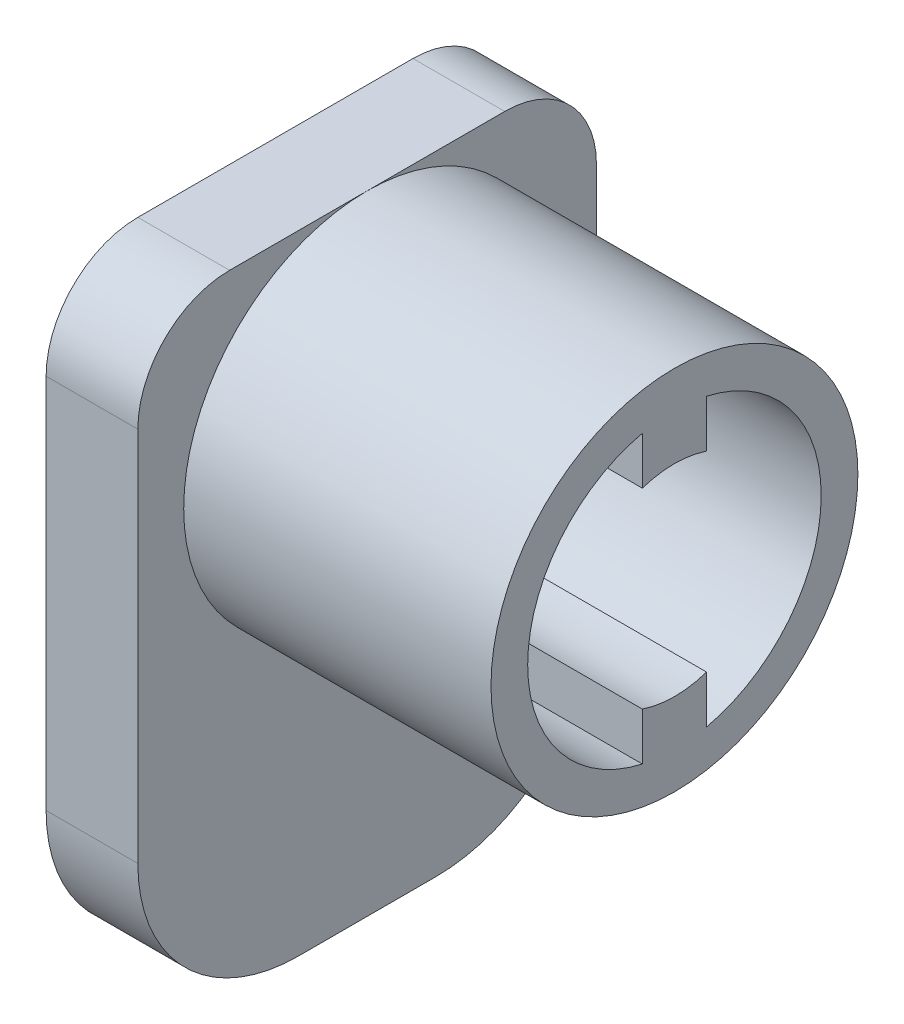
SolidWorks part; units mm, degrees
ref_plane "Front Plane" through (0, 0, 0) normal (0, 0, 1) x (1, 0, 0)
ref_plane "Top Plane" through (0, 0, 0) normal (0, 1, 0) x (1, 0, 0)
ref_plane "Right Plane" through (0, 0, 0) normal (1, 0, 0) x (0, 0, -1)
sketch "Sketch2" plane through (0, 0, 0) normal (1, 0, 0) x (0, 0, -1)
  circle A0 centre (0, 0) radius 4
  dimension "D1" = 8
extrude "Boss-Extrude1" add sketch "Sketch2" against normal blind 6.7
sketch "Sketch3" plane through (-6.7, 0, 0) normal (-1, 0, 0) x (0, 0, 1)
  line L0 (0, 0) -> (0, -9.7) construction
  line L1 (-5, 4) -> (5, 4)
  line L2 (-5, 4) -> (-5, -9.7)
  line L3 (-5, -9.7) -> (5, -9.7)
  line L4 (5, 4) -> (5, -9.7)
  dimension "D1" = 9.7
  dimension "D2" = 4
  dimension "D3" = 10
extrude "Boss-Extrude2" add sketch "Sketch3" along normal blind 2
sketch "Sketch4" plane through (0, 0, 0) normal (1, 0, 0) x (0, 0, -1)
  circle A0 centre (0, 0) radius 3.2
  dimension "D1" = 6.4
extrude "Cut-Extrude1" cut sketch "Sketch4" against normal up to surface (6.7 mm away) up to face at (-6.7, -1.2333, -0.6667)
sketch "Sketch6" plane through (-8.7, 0, 0) normal (-1, 0, 0) x (0, 0, 1)
  line L6 (0.7, -2.8618) -> (0.7, -1.7861)
  line L7 (0.7, -2.8618) -> (0.7, -2.0857)
  line L8 (-0.7, -2.8618) -> (0.7, -2.8618) construction
  line L9 (-0.7, -1.7861) -> (-0.7, -2.8618)
  line L10 (-0.7, -2.0857) -> (-0.7, -2.8618)
  line L12 (0, 0) -> (5, 0) construction
  line L13 (5, -9.7) -> (5, 4) construction
  line L15 (-0.7, 2.0857) -> (-0.7, 2.8618)
  line L16 (-0.7, 2.8618) -> (0.7, 2.8618) construction
  line L17 (0.7, 2.8618) -> (0.7, 2.0857)
  line L18 (-0.7, -2.8618) -> (-0.7, -3.1225)
  line L19 (0.7, -2.8618) -> (0.7, -3.1225)
  line L20 (-0.7, 2.8618) -> (-0.7, 3.1225)
  line L21 (0.7, 2.8618) -> (0.7, 3.1225)
  arc A1 (-0.7, 2.0857) -> (0.7, 2.0857) centre (0, 0) cw
  arc A2 (-0.99, -1.9647) -> (0.99, -1.9647) centre (0, 0) ccw
  arc A3 (-0.7, -2.0857) -> (0.7, -2.0857) centre (0, 0) ccw
  circle A4 centre (0, 0) radius 3.2 construction
  arc A5 (-0.7, -3.1225) -> (0.7, -3.1225) centre (0, 0) ccw
  arc A6 (-0.7, 3.1225) -> (0.7, 3.1225) centre (0, 0) cw
  dimension "D3" = 0.2
  dimension "D1" = 0.2
  dimension "D2" = 0.2
sketch "Sketch7" plane through (-8.7, 0, 0) normal (-1, 0, 0) x (0, 0, 1)
  circle A0 centre (0, 0) radius 1.6
  dimension "D1" = 3.2
extrude "Cut-Extrude4" cut sketch "Sketch7" against normal through all
extrude "Boss-Extrude3" add sketch "Sketch6" against normal up to surface (8.7 mm away) up to face at (0, 0, -3.2)
fillet "Fillet2" radius 2 2 edges at (-7.7, 4, 5) (-7.7, 4, -5)
fillet "Fillet3" radius 3.5 2 edges at (-7.7, -9.7, -5) (-7.7, -9.7, 5)
